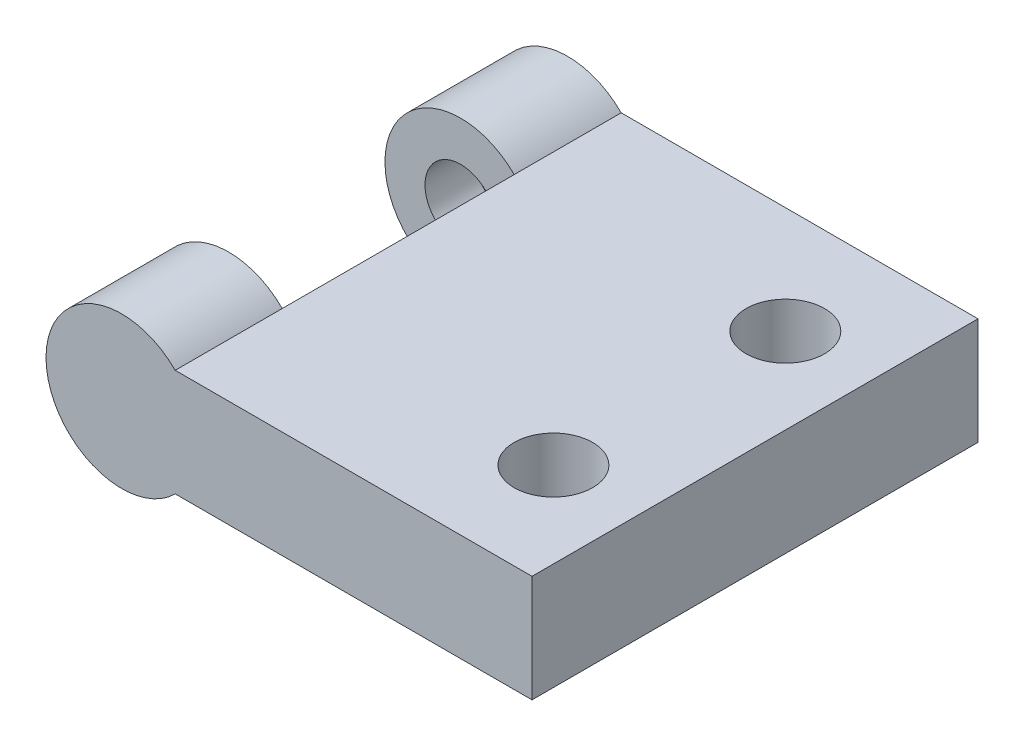
SolidWorks part; units mm, degrees
ref_plane "Front Plane" through (0, 0, 0) normal (0, 0, 1) x (1, 0, 0)
ref_plane "Top Plane" through (0, 0, 0) normal (0, 1, 0) x (1, 0, 0)
ref_plane "Right Plane" through (0, 0, 0) normal (1, 0, 0) x (0, 0, -1)
sketch "Sketch2" plane through (0, 0, 0) normal (0, 1, 0) x (1, 0, 0)
  line L0 (0, 0) -> (12.7, 0)
  line L1 (12.7, 0) -> (12.7, 15.875)
  line L2 (12.7, 15.875) -> (0, 15.875)
  line L3 (0, 15.875) -> (0, 0)
extrude "Boss-Extrude1" add sketch "Sketch2" along normal blind 3.81
sketch "Sketch3" plane through (0, 3.81, 0) normal (0, 1, 0) x (1, 0, 0)
  line L0 (12.7, 0) -> (9.652, 0)
  line L1 (0, 0) -> (12.7, 0) construction
  circle A0 centre (9.652, 12.065) radius 1.397
  circle A1 centre (9.652, 3.81) radius 1.397
extrude "Cut-Extrude1" cut sketch "Sketch3" against normal blind 3.81 contours A1 | A0
sketch "Sketch6" plane through (0, 0, 0) normal (0, 0, 1) x (1, 0, 0)
  line L0 (0, 0) -> (0, 1.905)
  line L1 (0, 1.905) -> (-1.905, 1.905)
  circle A0 centre (-1.905, 1.905) radius 2.6941
extrude "Boss-Extrude2" add sketch "Sketch6" against normal blind 3.81
sketch "Sketch8" plane through (0, 0, -3.81) normal (0, 0, -1) x (-1, 0, 0)
  circle A1 centre (1.905, 1.905) radius 2.6941
  circle A2 centre (1.905, 1.905) radius 1.27
extrude "Cut-Extrude3" cut sketch "Sketch8" against normal blind 1.778 contours A2
sketch "Sketch9" plane through (0, 0, -15.875) normal (0, 0, -1) x (-1, 0, 0)
  line L0 (0, 0) -> (0, 1.905)
  line L1 (0, 3.81) -> (0, 0) construction
  line L2 (0, 1.905) -> (1.905, 1.905)
  circle A0 centre (1.905, 1.905) radius 2.6941
extrude "Boss-Extrude3" add sketch "Sketch9" against normal blind 3.81
sketch "Sketch10" plane through (0, 0, -12.065) normal (0, 0, 1) x (1, 0, 0)
  circle A0 centre (-1.905, 1.905) radius 2.6941
  circle A1 centre (-1.905, 1.905) radius 1.27
extrude "Cut-Extrude4" cut sketch "Sketch10" against normal blind 1.778 contours A1
